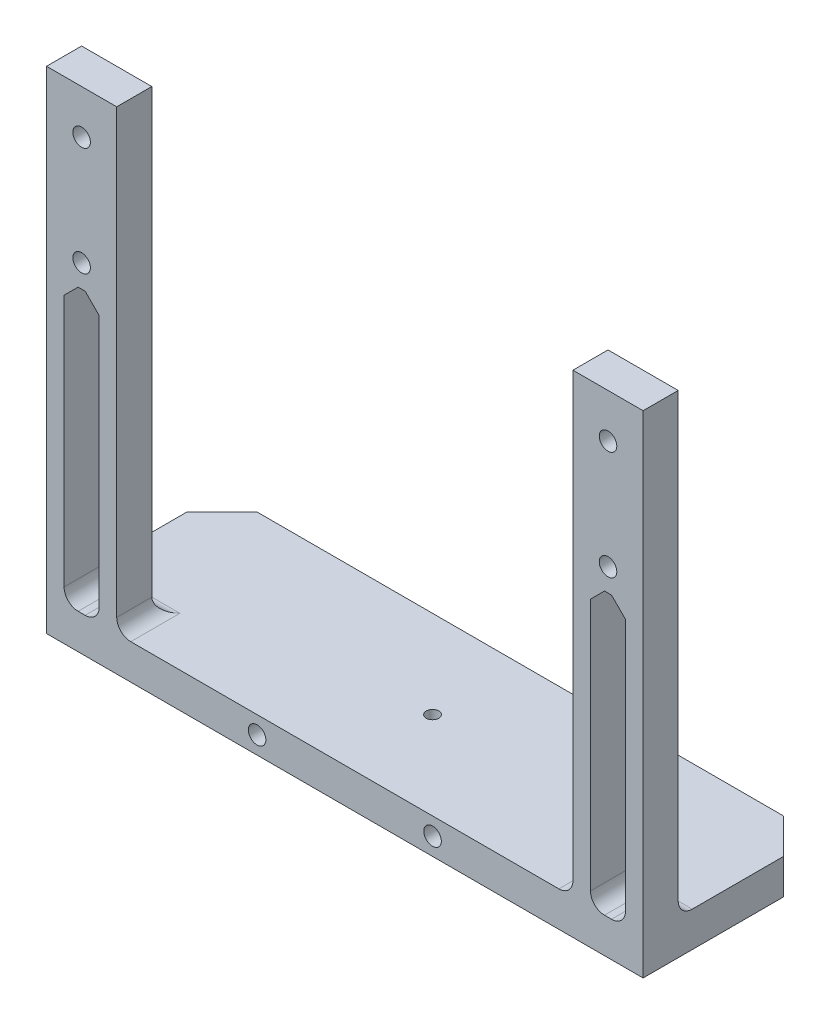
SolidWorks part; units mm, degrees
ref_plane "Front Plane" through (0, 0, 0) normal (0, 0, 1) x (1, 0, 0)
ref_plane "Top Plane" through (0, 0, 0) normal (0, 1, 0) x (1, 0, 0)
ref_plane "Right Plane" through (0, 0, 0) normal (1, 0, 0) x (0, 0, -1)
sketch "Sketch1" plane through (0, 0, 0) normal (0, 0, 1) x (1, 0, 0)
  line L0 (-32.5, 0) -> (32.5, 0)
  line L1 (32.5, 0) -> (32.5, 65)
  line L2 (32.5, 65) -> (42.5, 65)
  line L3 (42.5, 65) -> (42.5, 0)
  line L4 (42.5, 0) -> (42.5, -5)
  line L5 (42.5, -5) -> (-42.5, -5)
  line L6 (0, 90.1489) -> (0, -19.4319) construction
  line L7 (37.5, 65) -> (37.5, 58.75) construction
  line L8 (37.5, 58.75) -> (37.5, 43.25) construction
  line L9 (37.5, 43.25) -> (37.5, 37) construction
  line L10 (-42.5, 0) -> (-42.5, -5)
  line L11 (-42.5, 65) -> (-42.5, 0)
  line L12 (-37.5, 43.25) -> (-37.5, 37) construction
  line L13 (-37.5, 65) -> (-37.5, 58.75) construction
  line L14 (-32.5, 65) -> (-42.5, 65)
  line L15 (-32.5, 0) -> (-32.5, 65)
  circle A0 centre (37.5, 58.75) radius 1.25
  circle A1 centre (37.5, 43.25) radius 1.25
  circle A2 centre (-37.5, 58.75) radius 1.25
  circle A3 centre (-37.5, 43.25) radius 1.25
  point P24 (0, 0)
  point P25 (0, -5)
  dimension "D1" = 32.5
  dimension "D2" = 65
  dimension "D3" = 10
  dimension "D4" = 5
  dimension "D5" = 65
  dimension "D6" = 6.25
  dimension "D7" = 15.5
  dimension "D8" = 6.25
extrude "Boss-Extrude1" add sketch "Sketch1" along normal blind 5
sketch "Sketch2" plane through (0, 0, 0) normal (0, 0, -1) x (-1, 0, 0)
  line L0 (42.5, 65) -> (42.5, -5) construction
  line L1 (-42.5, -5) -> (42.5, -5)
  line L2 (-42.5, -5) -> (-42.5, 0)
  line L3 (-42.5, 0) -> (42.5, 0)
  line L4 (42.5, -5) -> (42.5, 0)
extrude "Boss-Extrude2" add sketch "Sketch2" along normal blind 20
fillet "Fillet1" radius 2 4 edges
sketch "Sketch8" plane through (0, 0, 5) normal (0, 0, 1) x (1, 0, 0)
  line L0 (-42.5, 21.934) -> (-40, 21.934) construction
  line L1 (-42.5, 65) -> (-42.5, -5) construction
  line L2 (-32.5, 28.5152) -> (-35, 28.5152) construction
  line L3 (-32.5, 2) -> (-32.5, 65) construction
  line L5 (-38, 0) -> (-37, 0)
  line L6 (-35, 2) -> (-35, 38)
  line L7 (-37, 40) -> (-38, 40)
  line L8 (-40, 38) -> (-40, 2)
  line L9 (-38, 40) -> (-40, 38)
  line L10 (-35, 38) -> (-37, 40)
  line L11 (0, 0) -> (0, 28.5152) construction
  line L12 (30.5, 0) -> (-30.5, 0) construction
  line L13 (38, 0) -> (37, 0)
  line L14 (35, 38) -> (37, 40)
  line L15 (37, 40) -> (38, 40)
  line L16 (38, 40) -> (40, 38)
  line L17 (40, 38) -> (40, 2)
  line L18 (35, 2) -> (35, 38)
  arc A0 (-37, 0) -> (-35, 2) centre (-37, 2) ccw
  arc A1 (-38, 0) -> (-40, 2) centre (-38, 2) cw
  arc A2 (38, 0) -> (40, 2) centre (38, 2) ccw
  arc A3 (37, 0) -> (35, 2) centre (37, 2) cw
  point P12 (-35, 40)
  point P13 (-40, 40)
  point P15 (-35, 0)
  dimension "D2" = 2
  dimension "D1" = 40
extrude "Cut-Extrude1" cut sketch "Sketch8" against normal blind 25
sketch "Sketch9" plane through (0, 0, -20) normal (0, 0, -1) x (-1, 0, 0)
  line L0 (-12.5, -2.5) -> (12.5, -2.5) construction
  line L3 (0, 0) -> (0, -5) construction
  line L4 (42.5, 0) -> (-42.5, 0) construction
  line L5 (-42.5, -5) -> (42.5, -5) construction
  circle A0 centre (12.5, -2.5) radius 1.25
  circle A1 centre (-12.5, -2.5) radius 1.25
  point P5 (0, -2.5)
  dimension "D2" = 2.5
  dimension "D1" = 12.5
extrude "Cut-Extrude2" cut sketch "Sketch9" against normal blind 58
sketch "Sketch10" plane through (0, -5, 0) normal (0, -1, 0) x (1, 0, 0)
  line L0 (42.5, -7.5) -> (-42.5, -7.5) construction
  line L1 (42.5, 5) -> (42.5, -20) construction
  line L2 (-42.5, 5) -> (-42.5, -20) construction
  line L3 (0, -20) -> (0, 5) construction
  line L4 (42.5, -20) -> (-42.5, -20) construction
  line L5 (-42.5, 5) -> (42.5, 5) construction
  circle A0 centre (0, -7.5) radius 1.95
  dimension "D1" = 3.9
extrude "Cut-Extrude3" cut sketch "Sketch10" against normal blind 2.9
sketch "Sketch11" plane through (0, -2.1, 0) normal (0, -1, 0) x (1, 0, 0)
  circle A0 centre (0, -7.5) radius 0.9
extrude "Cut-Extrude4" cut sketch "Sketch11" against normal blind 6.9
chamfer "Chamfer1" distance 5 angle 45 2 edges at (-42.5, -2.5, -20) (42.5, -2.5, -20)
